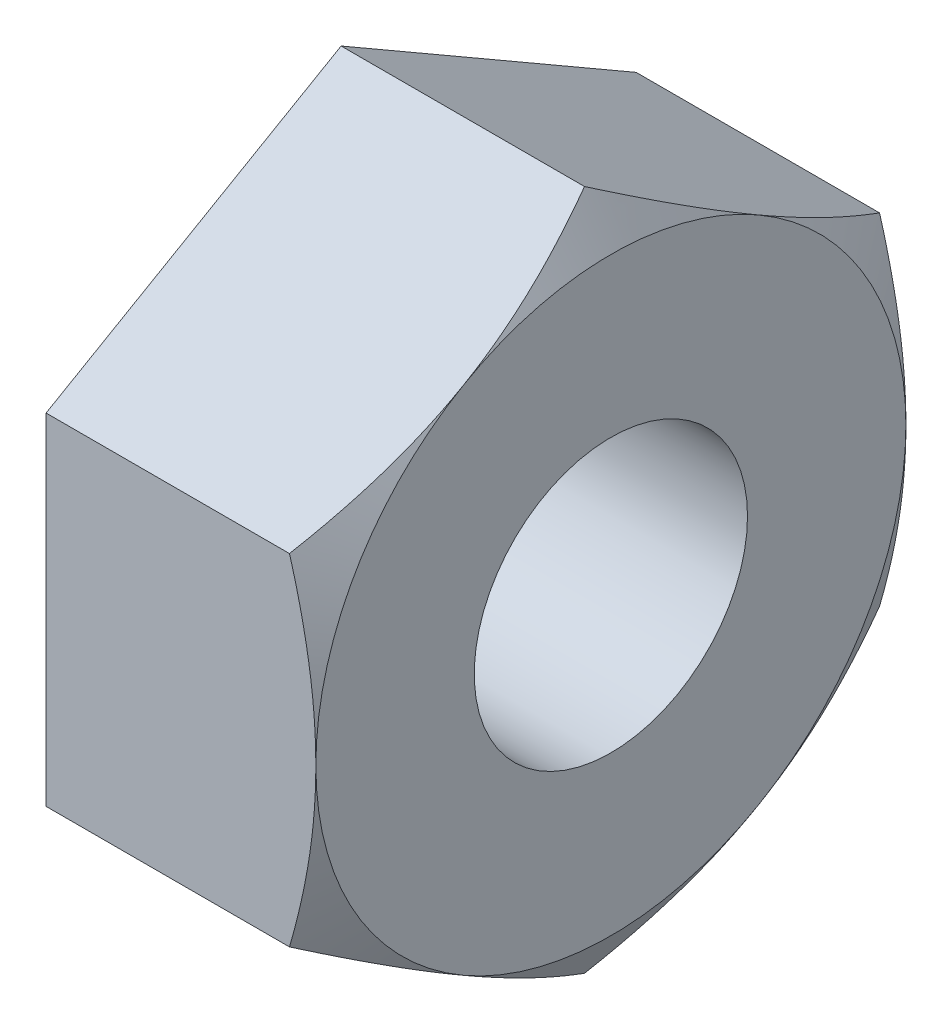
SolidWorks part; units mm, degrees
ref_plane "Front Plane" through (0, 0, 0) normal (0, 0, 1) x (1, 0, 0)
ref_plane "Top Plane" through (0, 0, 0) normal (0, 1, 0) x (1, 0, 0)
ref_plane "Right Plane" through (0, 0, 0) normal (1, 0, 0) x (0, 0, -1)
sketch "Sketch1" plane through (0, 0, 0) normal (1, 0, 0) x (0, 0, -1)
  line L1 (0, 4.0415) -> (-3.5, 2.0207)
  line L2 (-3.5, 2.0207) -> (-3.5, -2.0207)
  line L3 (-3.5, -2.0207) -> (0, -4.0415)
  line L4 (0, -4.0415) -> (3.5, -2.0207)
  line L5 (3.5, -2.0207) -> (3.5, 2.0207)
  line L6 (3.5, 2.0207) -> (0, 4.0415)
  circle A0 centre (0, 0) radius 3.5 construction
  dimension "FIX_1" = 7
extrude "Boss-Extrude1" add sketch "Sketch1" against normal blind 3.2
sketch "Sketch2" plane through (0, 0, 0) normal (0, 0, 1) x (1, 0, 0)
  line L5 (0, 3.5) -> (-0.3126, 4.0415)
  line L6 (0, 4.0415) -> (0, 2.0207) construction
  line L7 (-0.3126, 4.0415) -> (0, 4.0415)
  line L8 (0, 4.0415) -> (0, 3.5)
  line L9 (-0.3126, 0) -> (0, 0) construction
  dimension "FIX_3" = 30
  dimension "FIX_4" = 7
revolve "Cut-Revolve1" cut sketch "Sketch2" angle 360 about L9
hole_wizard "Tap1" positions "Sketch4" profile "Sketch3" hole size "M4x0.7" standard "JIS" end condition through all
sketch "Sketch4" plane through (0, 0, 0) normal (1, 0, 0) x (0, 0, -1)
  point P0 (0, 0)
cosmetic thread "Thread301" parameters "NFIX_1"=4
sketch "Sketch3" plane through (0, 0, 0) normal (0, 1, 0) x (0, 0, -1)
  line L0 (0, 0) -> (0, 3.2)
  line L1 (0, 3.2) -> (1.621, 3.2)
  line L2 (1.621, 3.2) -> (1.621, 0)
  line L5 (1.621, 0) -> (0, 0)
  line L11 (0, -6.35) -> (0, 107.95) construction
  dimension "FIX_6" = 3.242
  dimension "Thru Hole Depth" = 3.2
